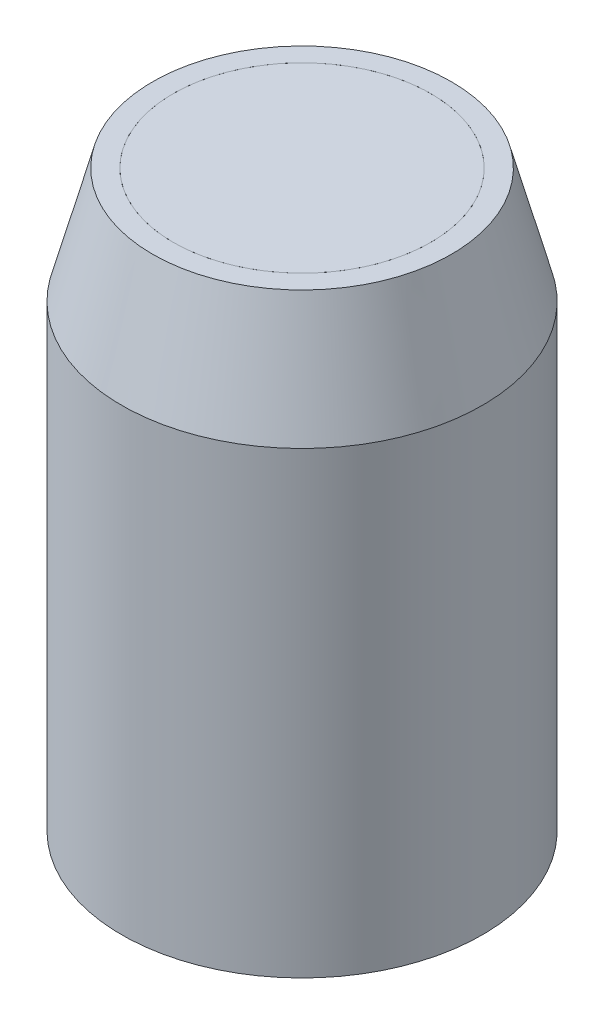
SolidWorks part; units mm, degrees
material "PLA"
ref_plane "Front Plane" through (0, 0, 0) normal (0, 0, 1) x (1, 0, 0)
ref_plane "Top Plane" through (0, 0, 0) normal (0, 1, 0) x (1, 0, 0)
ref_plane "Right Plane" through (0, 0, 0) normal (1, 0, 0) x (0, 0, -1)
sketch "Sketch1" plane through (0, 0, 0) normal (0, 1, 0) x (1, 0, 0)
  circle A0 centre (0, 0) radius 5
  dimension "D1" = 10
extrude "Boss-Extrude1" add sketch "Sketch1" along normal blind 19.8745
sketch "Sketch2" plane through (0, 0, 0) normal (0, 0, 1) x (1, 0, 0)
  line L0 (0, 0) -> (-5, 0)
  line L1 (-5, 0) -> (5, 0) construction
  line L2 (-5, 0) -> (-5, 19.8745)
  line L3 (-5, 19.8745) -> (-5.8, 19.8745)
  line L4 (-5.8, 19.8745) -> (-7, 15.396)
  line L5 (-7, 15.396) -> (-7, -2.4)
  line L6 (-7, -2.4) -> (0, -2.4)
  line L7 (0, -2.4) -> (0, 0)
  line L8 (-5, 19.8745) -> (-5, 0) construction
  line L9 (5, 19.8745) -> (-5, 19.8745) construction
  line L10 (0, 0) -> (0, 19.8745) construction
  dimension "D1" = 2
  dimension "D2" = 2.4
  dimension "D3" = 15
  dimension "D4" = 0.8
revolve "Revolve1" add sketch "Sketch2" angle 360 about L10
equation "\"Charge mass\"= 1'Mass in grams"
equation "\"Charge volume\"= \"Charge mass\" / 0.000640642'Volume in mm^3"
equation "\"Charge height\"= \"Charge volume\" / ( pi * ( 5 ) ^ 2 )"
equation "\"D1@Boss-Extrude1\"= \"Charge height\""
